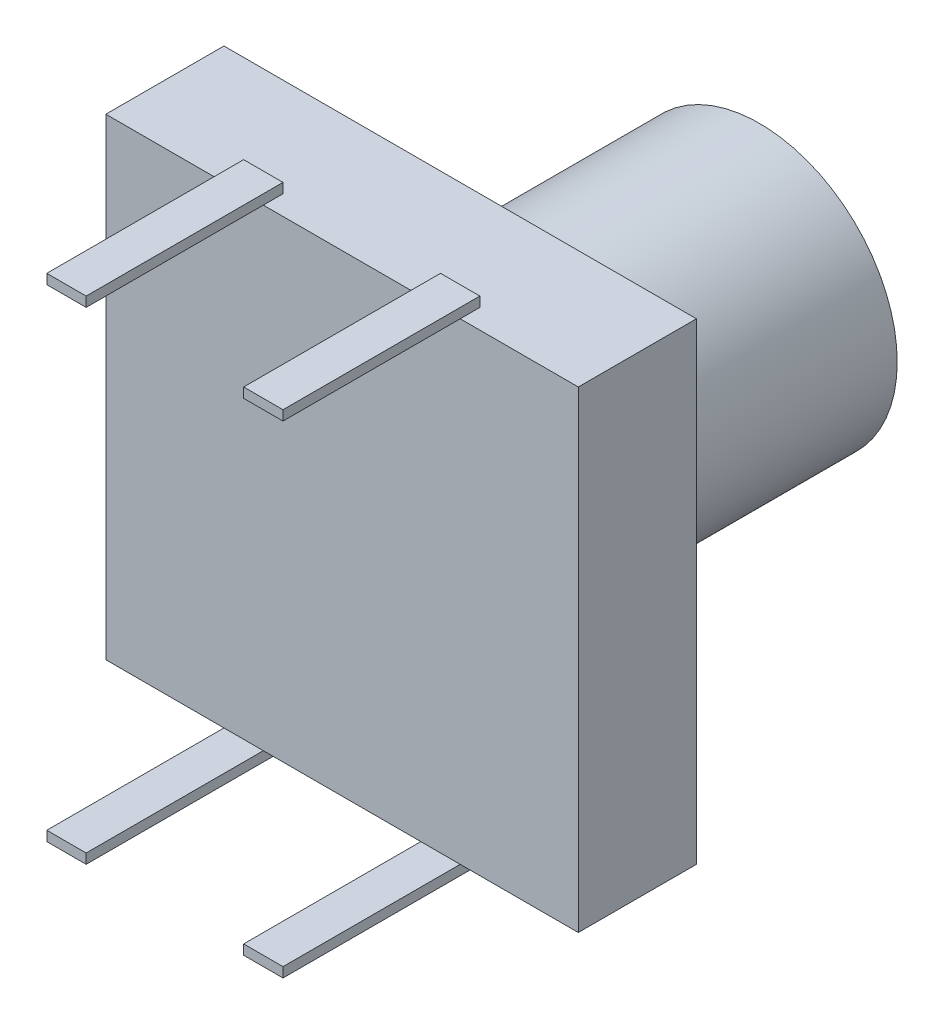
SolidWorks part; units mm, degrees
ref_plane "Front Plane" through (0, 0, 0) normal (0, 0, 1) x (1, 0, 0)
ref_plane "Top Plane" through (0, 0, 0) normal (0, 1, 0) x (1, 0, 0)
ref_plane "Right Plane" through (0, 0, 0) normal (1, 0, 0) x (0, 0, -1)
sketch "Sketch1" plane through (0, 0, 0) normal (0, 0, 1) x (1, 0, 0)
  line L1 (-6, -6) -> (6, -6)
  line L2 (-6, -6) -> (-6, 6)
  line L3 (-6, 6) -> (6, 6)
  line L4 (6, -6) -> (6, 6)
  line L5 (-6, -6) -> (6, 6) construction
  line L6 (-6, 6) -> (6, -6) construction
  point P0 (0, 0)
  dimension "D1" = 12
extrude "Boss-Extrude1" add sketch "Sketch1" along normal blind 3 contours L4 L3 L2 L1
sketch "Sketch4" plane through (0, 0, 0) normal (0, 0, -1) x (-1, 0, 0)
  line L8 (-5, -5) -> (5, -5)
  line L9 (5, -5) -> (5, 5)
  line L10 (5, 5) -> (-5, 5)
  line L11 (-5, 5) -> (-5, -5)
  line L12 (-5, -5) -> (5, -5)
  line L13 (5, -5) -> (5, 5)
  line L14 (5, 5) -> (-5, 5)
  line L15 (-5, 5) -> (-5, -5)
  dimension "D1" = 1
extrude "Boss-Extrude2" add sketch "Sketch4" along normal blind 0.1
sketch "Sketch5" plane through (0, 0, -0.1) normal (0, 0, -1) x (-1, 0, 0)
  circle A0 centre (4.3144, 4.2997) radius 0.5
  dimension "D1" = 1
extrude "Boss-Extrude3" add sketch "Sketch5" along normal blind 0.25
sketch "Sketch7" plane through (-0.1827, -0.9284, -0.1) normal (0, 0, -1) x (-1, 0, 0)
  circle A0 centre (4.0843, -3.3838) radius 0.5
  dimension "D1" = 1
extrude "Boss-Extrude4" add sketch "Sketch7" along normal blind 0.25
mirror "Mirror1" about plane through (0, 0, 0) normal (1, 0, 0) of "Boss-Extrude4", "Boss-Extrude3"
sketch "Sketch9" plane through (0, 0, -0.1) normal (0, 0, -1) x (-1, 0, 0)
  circle A0 centre (0, 0) radius 3.5
  dimension "D1" = 7
extrude "Boss-Extrude5" add sketch "Sketch9" along normal blind 7.5 contours A0
sketch "Sketch10" plane through (0, -6, 0) normal (0, -1, 0) x (1, 0, 0)
  line L0 (6, 3) -> (6, 0) construction
  line L1 (3, 2.5) -> (2, 2.5)
  line L2 (3, 2.5) -> (3, 7.5)
  line L3 (3, 7.5) -> (2, 7.5)
  line L4 (2, 2.5) -> (2, 7.5)
  line L5 (-6, 0) -> (6, 0) construction
  dimension "D1" = 3
  dimension "D2" = 2.5
  dimension "D3" = 1
  dimension "D4" = 5
extrude "Boss-Extrude6" add sketch "Sketch10" along normal blind 0.25
mirror "Mirror2" about plane through (0, 0, 0) normal (1, 0, 0) of "Boss-Extrude6"
mirror "Mirror3" about plane through (0, 0, 0) normal (0, 1, 0) of "Mirror2", "Boss-Extrude6"
